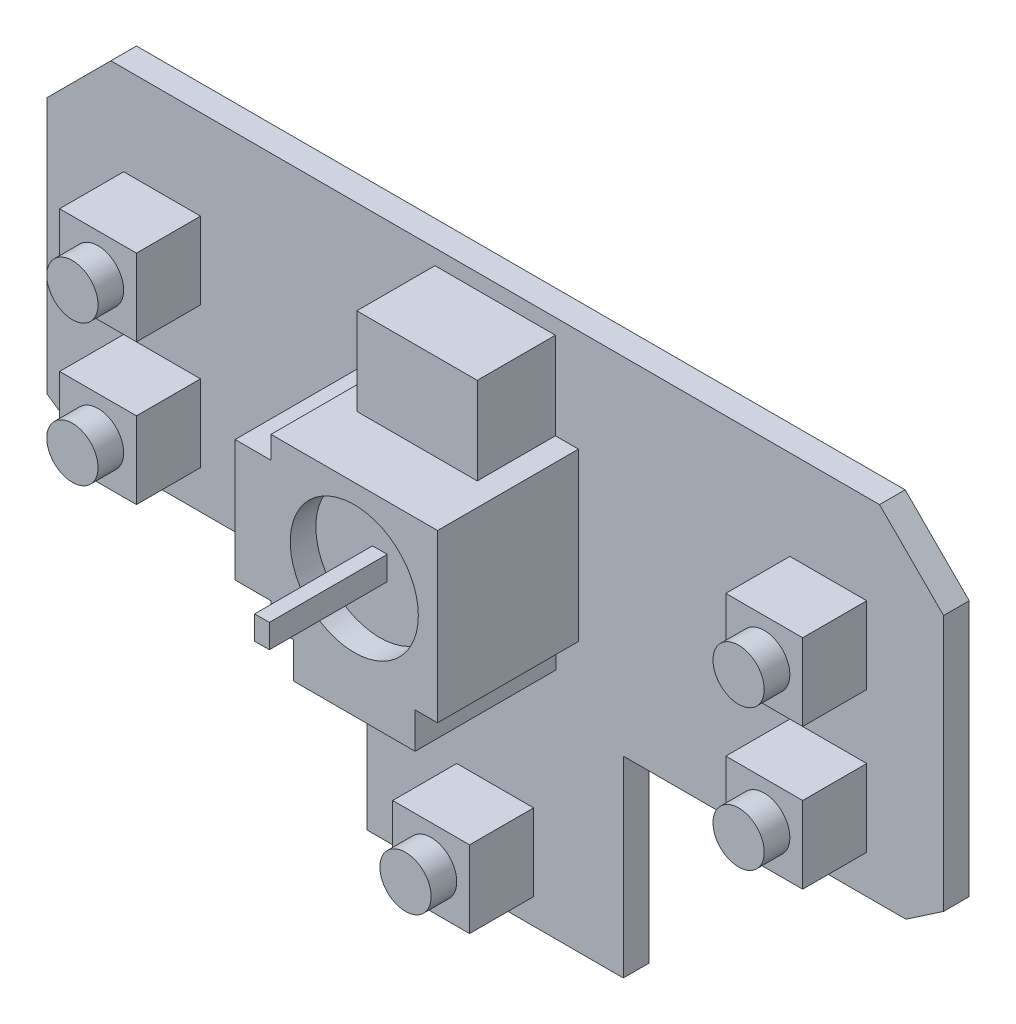
SolidWorks part; units mm, degrees
ref_plane "Plan de face" through (0, 0, 0) normal (0, 0, 1) x (1, 0, 0)
ref_plane "Plan de dessus" through (0, 0, 0) normal (0, 1, 0) x (1, 0, 0)
ref_plane "Plan de droite" through (0, 0, 0) normal (1, 0, 0) x (0, 0, -1)
sketch "Esquisse1" plane through (0, 0, 0) normal (0, 0, 1) x (1, 0, 0)
  line L0 (2.9412, -27) -> (25, -27)
  line L3 (25, -42) -> (2.9412, -27) construction
  line L4 (25, -42) -> (45, -42)
  line L5 (45, -42) -> (67.0588, -27) construction
  line L7 (25, -27) -> (25, -42)
  line L8 (45, -42) -> (45, -27)
  line L9 (45, -27) -> (67.0588, -27)
  line L10 (0, -25) -> (2.9412, -27)
  line L11 (67.0588, -27) -> (70, -25)
  line L12 (0, -5) -> (5, 0)
  line L13 (65, 0) -> (70, -5)
  line L14 (5, 0) -> (65, 0)
  line L15 (70, -5) -> (70, -25)
  line L16 (0, -25) -> (0, -5)
  dimension "D1" = 5
  dimension "D2" = 20
  dimension "D3" = 5
  dimension "D4" = 25
  dimension "D5" = 42
  dimension "D6" = 5
  dimension "D7" = 5
  dimension "D8" = 70
  dimension "D9" = 15
extrude "Extrusion1" add sketch "Esquisse1" against normal blind 2
sketch "Esquisse2" plane through (0, 0, 0) normal (0, 0, 1) x (1, 0, 0)
  line L0 (0, -5) -> (0, -25) construction
  line L1 (28.5, -8) -> (41.5, -8)
  line L2 (28.5, -8) -> (28.5, -21)
  line L3 (28.5, -21) -> (41.5, -21)
  line L4 (41.5, -8) -> (41.5, -21)
  line L5 (65, 0) -> (5, 0) construction
  line L6 (28.5, -21) -> (41.5, -8) construction
  line L7 (28.5, -8) -> (41.5, -21) construction
  point P8 (35, -14.5)
  dimension "D1" = 14.5
  dimension "D2" = 13
  dimension "D3" = 13
  dimension "D4" = 35
extrude "Extrusion2" add sketch "Esquisse2" along normal blind 11
sketch "Esquisse7" plane through (0, 0, 0) normal (0, 0, 1) x (1, 0, 0)
  line L5 (28.5, -8) -> (28.5, -21) construction
  line L6 (41.5, -8) -> (28.5, -8) construction
  line L7 (30.3, -8) -> (39.7, -8)
  line L8 (30.3, -8) -> (30.3, -1.2)
  line L9 (30.3, -1.2) -> (39.7, -1.2)
  line L10 (39.7, -8) -> (39.7, -1.2)
  point P0 (28.5, -14.5)
  dimension "D1" = 13.3
  dimension "D5" = 1.8
  dimension "D6" = 9.4
extrude "Extrusion7" add sketch "Esquisse7" along normal blind 6.1
sketch "Esquisse8" plane through (0, 0, 0) normal (0, 0, 1) x (1, 0, 0)
  line L0 (28.5, -21) -> (41.5, -21) construction
  line L1 (25.7, -9.75) -> (28.5, -9.75)
  line L2 (25.7, -9.75) -> (25.7, -19.25)
  line L3 (25.7, -19.25) -> (28.5, -19.25)
  line L4 (28.5, -9.75) -> (28.5, -19.25)
  line L6 (39.75, -23.8) -> (30.25, -23.8)
  line L7 (39.75, -23.8) -> (39.75, -21)
  line L8 (39.75, -21) -> (30.25, -21)
  line L9 (30.25, -23.8) -> (30.25, -21)
  line L10 (28.5, -8) -> (28.5, -21) construction
  line L11 (41.5, -8) -> (28.5, -8) construction
  point P10 (35, -8)
  dimension "D1" = 9.3
  dimension "D2" = 1.75
  dimension "D3" = 1.75
  dimension "D4" = 9.5
extrude "Extrusion8" add sketch "Esquisse8" along normal blind 11
sketch "Esquisse6" plane through (0, 0, 11) normal (0, 0, 1) x (1, 0, 0)
  line L0 (28.5, -21) -> (41.5, -8) construction
  circle A0 centre (35, -14.5) radius 5
  dimension "D1" = 10
extrude "Extrusion6" cut sketch "Esquisse6" against normal blind 2
sketch "Esquisse3" plane through (0, 0, 0) normal (0, 0, 1) x (1, 0, 0)
  line L0 (6, -18) -> (12, -18)
  line L1 (6, -7) -> (12, -7)
  line L2 (6, -7) -> (6, -13)
  line L3 (6, -13) -> (12, -13)
  line L4 (12, -7) -> (12, -13)
  line L5 (6, -18) -> (6, -24)
  line L6 (6, -24) -> (12, -24)
  line L7 (12, -18) -> (12, -24)
  line L8 (32, -34) -> (38, -34)
  line L9 (32, -34) -> (32, -40)
  line L10 (32, -40) -> (38, -40)
  line L11 (38, -34) -> (38, -40)
  line L12 (58, -7) -> (64, -7)
  line L13 (58, -7) -> (58, -13)
  line L14 (58, -13) -> (64, -13)
  line L15 (64, -7) -> (64, -13)
  line L16 (58, -18) -> (64, -18)
  line L17 (58, -18) -> (58, -24)
  line L18 (58, -24) -> (64, -24)
  line L19 (64, -18) -> (64, -24)
  line L20 (6, -13) -> (6, -18) construction
  line L21 (58, -13) -> (58, -18) construction
  line L22 (12, -18) -> (58, -18) construction
  line L23 (65, 0) -> (5, 0) construction
  line L24 (12, -7) -> (58, -7) construction
  line L25 (12, -24) -> (32, -34) construction
  line L26 (38, -34) -> (58, -24) construction
  line L27 (25, -42) -> (45, -42) construction
  line L29 (70, -25) -> (70, -5) construction
  dimension "D1" = 6
  dimension "D2" = 7
  dimension "D3" = 6
  dimension "D4" = 6
  dimension "D7" = 5
  dimension "D11" = 2
extrude "Extrusion3" add sketch "Esquisse3" along normal blind 5
sketch "Esquisse5" plane through (0, 0, 5) normal (0, 0, 1) x (1, 0, 0)
  line L0 (6, -13) -> (12, -7) construction
  line L1 (6, -24) -> (12, -18) construction
  line L3 (38, -34) -> (32, -40) construction
  line L5 (58, -24) -> (64, -18) construction
  line L7 (58, -13) -> (64, -7) construction
  circle A0 centre (9, -10) radius 2
  circle A1 centre (9, -21) radius 2
  circle A2 centre (61, -21) radius 2
  circle A3 centre (61, -10) radius 2
  circle A4 centre (35, -37) radius 2
  dimension "D1" = 4
extrude "Extrusion5" add sketch "Esquisse5" along normal blind 2
sketch "Esquisse9" plane through (0, 0, 11) normal (0, 0, 1) x (1, 0, 0)
  line L0 (28.5, -21) -> (41.5, -8) construction
  line L1 (34.425, -13.575) -> (35.575, -13.575)
  line L2 (34.425, -13.575) -> (34.425, -15.425)
  line L3 (34.425, -15.425) -> (35.575, -15.425)
  line L4 (35.575, -13.575) -> (35.575, -15.425)
  line L5 (34.425, -13.575) -> (35.575, -15.425) construction
  line L6 (28.5, -8) -> (41.5, -21) construction
  line L7 (34.425, -15.425) -> (35.575, -13.575) construction
  point P12 (35, -14.5)
  point P13 (35, -14.5)
  dimension "D1" = 1.85
  dimension "D2" = 1.15
extrude "Extrusion9" add sketch "Esquisse9" along normal blind 7.2 and the other way up to next
